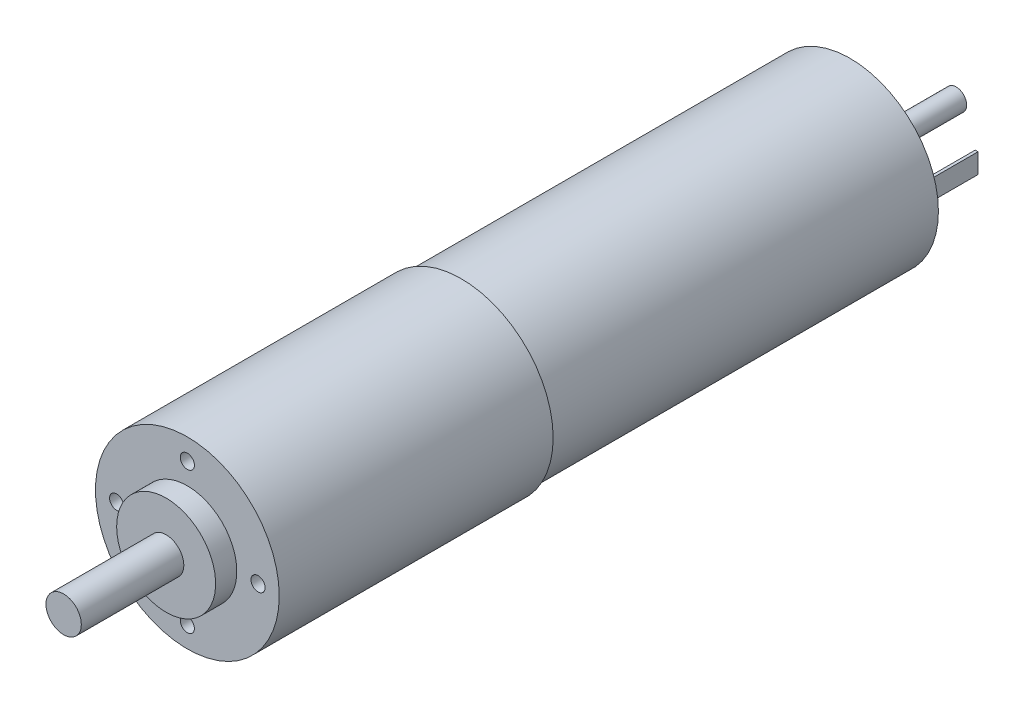
SolidWorks part; units mm, degrees
ref_plane "Front Plane" through (0, 0, 0) normal (0, 0, 1) x (1, 0, 0)
ref_plane "Top Plane" through (0, 0, 0) normal (0, 1, 0) x (1, 0, 0)
ref_plane "Right Plane" through (0, 0, 0) normal (1, 0, 0) x (0, 0, -1)
ref_plane "Plane1"
sketch "Sketch1" plane through (0, 0, 0) normal (0, 0, 1) x (1, 0, 0)
  circle A0 centre (0, 0) radius 12.5
  dimension "D1" = 25
extrude "Extrusion1" add sketch "Sketch1" along normal blind 55
sketch "Sketch2" plane through (0, 0, 55) normal (0, 0, 1) x (1, 0, 0)
  circle A0 centre (0, 0) radius 13
extrude "Extrusion2" add sketch "Sketch2" along normal blind 38.75
sketch "Sketch3" plane through (0, 0, 93.75) normal (0, 0, 1) x (1, 0, 0)
  circle A0 centre (0, 0) radius 7
  dimension "D1" = 14
extrude "Extrusion3" add sketch "Sketch3" along normal blind 3
sketch "Sketch4" plane through (0, 0, 96.75) normal (0, 0, 1) x (1, 0, 0)
  circle A0 centre (0, 0) radius 2.5
  dimension "D1" = 5
extrude "Extrusion4" add sketch "Sketch4" along normal blind 14.5
ref_plane "Plane2"
sketch "Sketch5" plane through (0, 0, 93.75) normal (0, 0, 1) x (1, 0, 0)
  circle A0 centre (0, 10) radius 1
  circle A1 centre (10, 0) radius 1
  circle A2 centre (0, -10) radius 1
  circle A3 centre (-10, 0) radius 1
  dimension "D1" = 2
  dimension "D2" = 2
  dimension "D3" = 2
  dimension "D4" = 2
extrude "Extrusion5" cut sketch "Sketch5" against normal blind 4 contours A0 | A1 | A2 | A3
sketch "Sketch6" plane through (0, 0, 0) normal (0, 0, -1) x (-1, 0, 0)
  circle A0 centre (0, 0) radius 4
  dimension "D1" = 8
extrude "Extrusion6" add sketch "Sketch6" along normal blind 2.75
ref_plane "Plane3"
sketch "Sketch7" plane through (0, 0, 0) normal (0, 0, -1) x (-1, 0, 0)
  circle A0 centre (0, 0) radius 1.5
  dimension "D1" = 3
extrude "Extrusion7" add sketch "Sketch7" along normal blind 15
ref_plane "Plane4"
sketch "Sketch8" plane through (0, 0, 0) normal (0, 0, -1) x (-1, 0, 0)
  line L0 (9, 1.4) -> (9.4, 1.4)
  line L1 (9.4, 1.4) -> (9.4, -1.4)
  line L2 (9.4, -1.4) -> (9, -1.4)
  line L3 (9, -1.4) -> (9, 1.4)
  line L4 (-9, 1.4) -> (-9.4, 1.4)
  line L5 (-9.4, 1.4) -> (-9.4, -1.4)
  line L6 (-9.4, -1.4) -> (-9, -1.4)
  line L7 (-9, -1.4) -> (-9, 1.4)
  dimension "D1" = 2.8
  dimension "D2" = 0.4
  dimension "D3" = 2.8
extrude "Extrusion8" add sketch "Sketch8" along normal blind 8.7 contours L3 L2 L1 L0 | L6 L7 L4 L5
